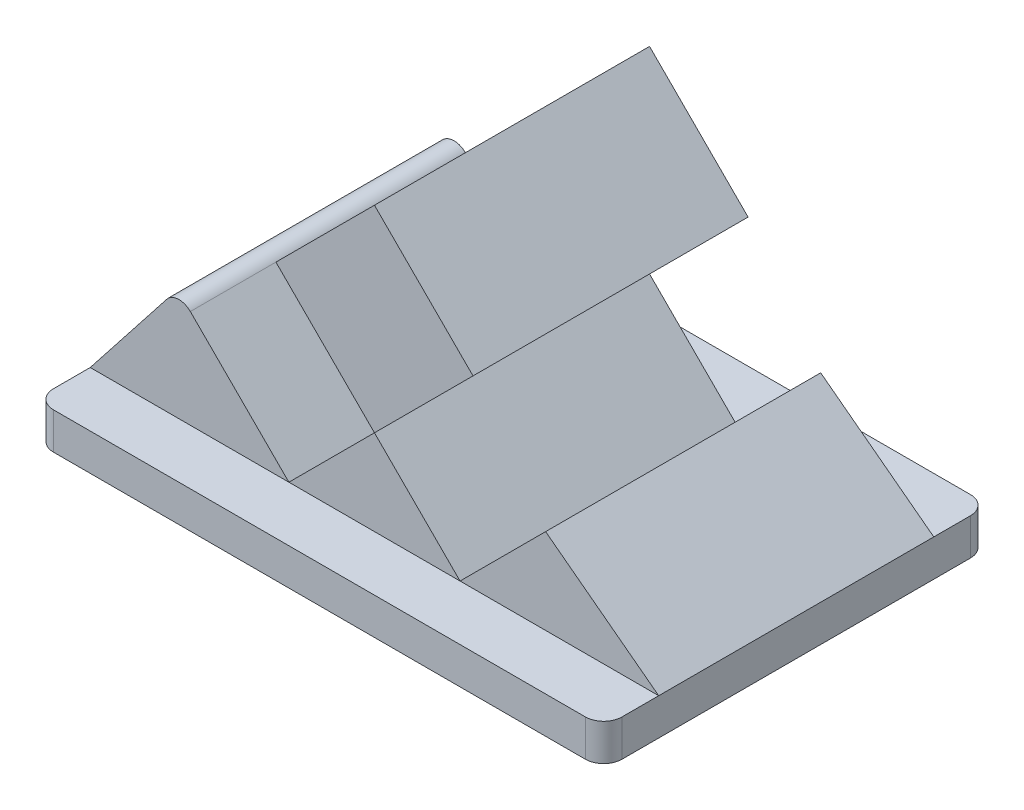
SolidWorks part; units mm, degrees
ref_plane "Front Plane" through (0, 0, 0) normal (0, 0, 1) x (1, 0, 0)
ref_plane "Top Plane" through (0, 0, 0) normal (0, 1, 0) x (1, 0, 0)
ref_plane "Right Plane" through (0, 0, 0) normal (1, 0, 0) x (0, 0, -1)
sketch "Sketch2" plane through (0, 0, 0) normal (0, 1, 0) x (1, 0, 0)
  line L1 (-145, 105) -> (145, 105)
  line L2 (-155, 95) -> (-155, -95)
  line L3 (-145, -105) -> (145, -105)
  line L4 (155, 95) -> (155, -95)
  line L5 (-155, 105) -> (155, -105) construction
  line L6 (-155, -105) -> (155, 105) construction
  arc A0 (-155, -95) -> (-145, -105) centre (-145, -95) ccw
  arc A1 (145, -105) -> (155, -95) centre (145, -95) ccw
  arc A2 (145, 105) -> (155, 95) centre (145, 95) cw
  arc A3 (-145, 105) -> (-155, 95) centre (-145, 95) ccw
  point P0 (0, 0)
  dimension "D3" = 10
  dimension "D1" = 310
  dimension "D2" = 210
extrude "Boss-Extrude1" add sketch "Sketch2" along normal blind 20
sketch "Sketch4" plane through (0, 0, 0) normal (0, 0, 1) x (1, 0, 0)
  line L0 (0, 0) -> (0, 131.0337) construction
  line L1 (0, 66.669) -> (-46.669, 20)
  line L2 (-145, 20) -> (145, 20) construction
  line L3 (-112.7576, 73.7401) -> (-155, 20)
  line L4 (-46.669, 20) -> (-100.4092, 73.7401)
  line L5 (0, 66.669) -> (46.669, 20)
  line L6 (-126.4318, 66.669) -> (196.1141, 66.669) construction
  line L7 (46.669, 20) -> (93.3381, 66.669)
  line L8 (155, 20) -> (93.3381, 66.669)
  line L13 (0, 66.669) -> (-53.7401, 120.4092)
  line L14 (0, 66.669) -> (53.7401, 120.4092)
  line L15 (-53.7401, 120.4092) -> (0, 174.1493)
  line L16 (0, 174.1493) -> (53.7401, 120.4092)
  line L20 (-155, 20) -> (155, 20)
  arc A0 (-100.4092, 73.7401) -> (-112.7576, 73.7401) centre (-106.5834, 67.5659) ccw
  point P9 (-100.4092, 73.7401)
  point P16 (0, 66.669)
  point P22 (-46.669, 20)
  dimension "D5" = 76
  dimension "D1" = 66
  dimension "D2" = 90
  dimension "D3" = 76
extrude "Boss-Extrude2" add sketch "Sketch4" along normal mid plane 150
sketch "Sketch7" plane through (0, 0, 0) normal (0, 0, 1) x (1, 0, 0)
  line L0 (-53.7401, 120.4092) -> (-107.4802, 174.1493)
  line L1 (-1.4142, 175.5635) -> (-53.7401, 227.8894)
  line L2 (53.7401, 120.4092) -> (107.4802, 174.1493)
  line L3 (0, 174.1493) -> (53.7401, 120.4092) construction
  line L4 (-53.7401, 120.4092) -> (0, 174.1493) construction
  line L5 (1.4142, 175.5635) -> (53.7401, 227.8894)
  line L6 (0, 66.669) -> (-53.7401, 120.4092) construction
  line L7 (0, 66.669) -> (53.7401, 120.4092) construction
  line L8 (-53.7401, 123.2376) -> (-106.066, 175.5635)
  line L9 (0, 176.9777) -> (52.3259, 229.3036)
  line L10 (0, 176.9777) -> (-52.3259, 229.3036)
  line L15 (53.7401, 123.2376) -> (106.066, 175.5635)
  line L17 (-106.066, 175.5635) -> (-107.4802, 174.1493)
  line L18 (52.3259, 229.3036) -> (53.7401, 227.8894)
  line L19 (-52.3259, 229.3036) -> (-53.7401, 227.8894)
  line L21 (107.4802, 174.1493) -> (106.066, 175.5635)
  line L25 (52.3259, 121.8234) -> (106.066, 175.5635) construction
  line L26 (0, 174.1493) -> (53.7401, 227.8894) construction
  line L27 (0, 176.9777) -> (55.1543, 121.8234)
  line L28 (-55.1543, 121.8234) -> (0, 176.9777)
  line L29 (1.4142, 175.5635) -> (53.7401, 123.2376)
  line L30 (-53.7401, 123.2376) -> (-1.4142, 175.5635)
  line L31 (0, 174.1493) -> (-53.7401, 227.8894) construction
  line L32 (-52.3259, 121.8234) -> (-106.066, 175.5635) construction
  dimension "D1" = 76
  dimension "D3" = 2
  dimension "D5" = 2
  dimension "D4" = 2
